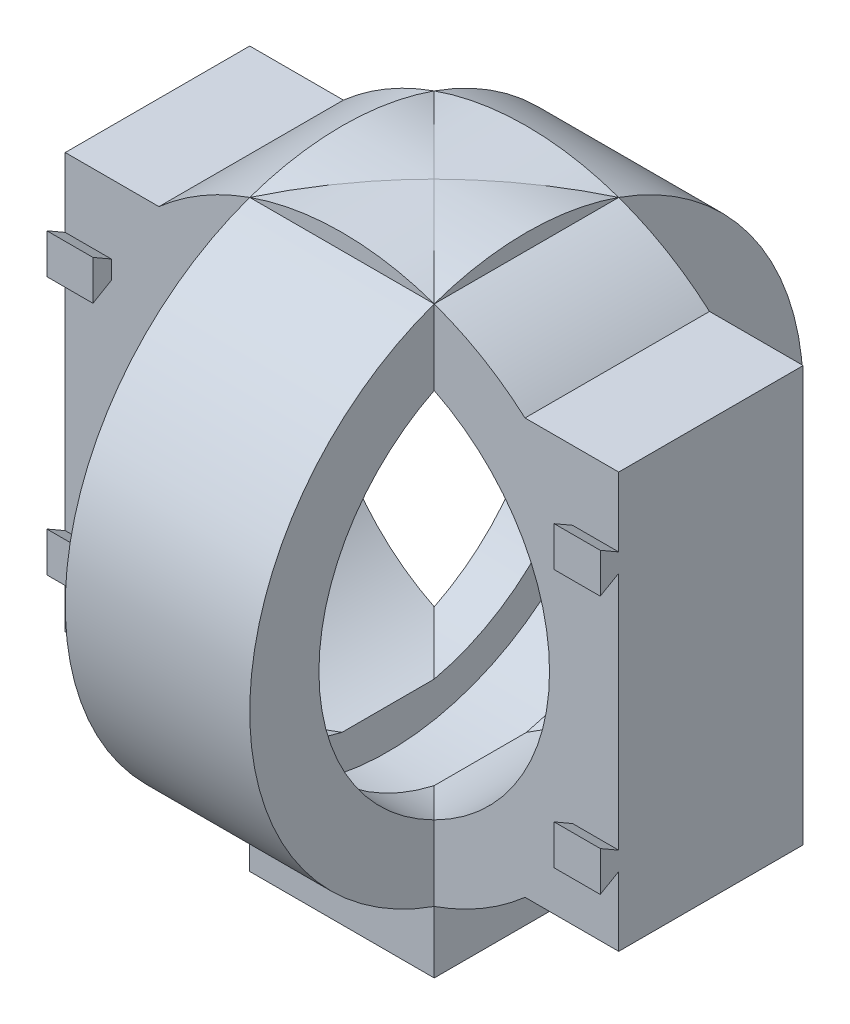
SolidWorks part; units mm, degrees
ref_plane "Plan de face" through (0, 0, 0) normal (0, 0, 1) x (1, 0, 0)
ref_plane "Plan de dessus" through (0, 0, 0) normal (0, 1, 0) x (1, 0, 0)
ref_plane "Plan de droite" through (0, 0, 0) normal (1, 0, 0) x (0, 0, -1)
sketch "Esquisse1" plane through (0, 0, 0) normal (0, 0, 1) x (1, 0, 0)
  circle A0 centre (0, 0) radius 60
  circle A1 centre (0, 0) radius 45
  dimension "D1" = 120
  dimension "D2" = 15
extrude "Boss.-Extru.1" add sketch "Esquisse1" along normal blind 40
ref_plane "Plan1" through (0, -60, 0) normal (0, -1, 0) x (-1, 0, 0)
ref_plane "Plan2" through (60, 0, 0) normal (1, 0, 0) x (0, 0, -1)
sketch "Esquisse5" plane through (60, 0, 0) normal (1, 0, 0) x (0, 0, -1)
  line L0 (-40, 60) -> (-40, -60) construction
  line L1 (-40, 45) -> (0, 45)
  line L2 (-40, 45) -> (-40, -45)
  line L3 (-40, -45) -> (0, -45)
  line L4 (0, 45) -> (0, -45)
  line L5 (0, -60) -> (0, 60) construction
  point P8 (0, 0)
extrude "Boss.-Extru.3" add sketch "Esquisse5" against normal up to surface (20.3137 mm away)
mirror "Symétrie2" about plane through (0, 0, 0) normal (1, 0, 0) of "Boss.-Extru.3"
sketch "Esquisse7" plane through (60, 0, 0) normal (1, 0, 0) x (0, 0, -1)
  line L0 (-40, 30) -> (-40, 26)
  line L1 (-40, 45) -> (-40, -45) construction
  line L2 (-40, 26) -> (-44, 23.6906)
  line L3 (-44, 23.6906) -> (-44, 32.3094)
  line L4 (-44, 32.3094) -> (-40, 30)
  line L5 (0, 0) -> (-40, 0) construction
  line L6 (0, -45) -> (0, 45) construction
  line L7 (-44, -32.3094) -> (-40, -30)
  line L8 (-44, -23.6906) -> (-44, -32.3094)
  line L9 (-40, -26) -> (-44, -23.6906)
  line L10 (-40, -30) -> (-40, -26)
  dimension "D1" = 60
  dimension "D2" = 60
  dimension "D3" = 4
  dimension "D4" = 4
  dimension "D5" = 26
extrude "Boss.-Extru.4" add sketch "Esquisse7" against normal blind 10 contours L4 L0 L2 L3 | L8 L7 L10 L9
mirror "Symétrie3" about plane through (0, 0, 0) normal (1, 0, 0) of "Boss.-Extru.4"
sketch "Esquisse9" plane through (0, 0, 0) normal (1, 0, 0) x (0, 0, -1)
  line L0 (-20, -67.3011) -> (-20, 64.0936) construction
  line L1 (-40, -45) -> (0, -45) construction
  point P4 (-20, -45)
pattern_circular "Répétition circulaire1" count 2 every 90 about axis through (0, -67.3011, 20) along (0, 1, 0) of "Boss.-Extru.1"
ref_plane "Plan3" through (0, 0, 20) normal (0, 0, 1) x (1, 0, 0)
sketch "Esquisse11" plane through (0, 0, 20) normal (0, 0, 1) x (1, 0, 0)
  line L0 (0, -67.3011) -> (0, 64.0936) construction
  line L1 (-10, -37.5) -> (10, -37.5)
  line L2 (-10, -37.5) -> (-10, -52.5)
  line L3 (-10, -52.5) -> (10, -52.5)
  line L4 (10, -37.5) -> (10, -52.5)
  line L5 (-20, 0) -> (20, 0) construction
  line L6 (-20, 56.5685) -> (-20, -56.5685) construction
  line L7 (20, -56.5685) -> (20, 56.5685) construction
  point P7 (0, -37.5)
  dimension "D1" = 15
  dimension "D2" = 52.5
  dimension "D3" = 20
revolve "Enlèvement de matière-Révolution3" cut sketch "Esquisse11" angle 360 about L5
sketch "Esquisse15" plane through (-60, 0, 0) normal (-1, 0, 0) x (0, 0, 1)
  line L0 (20, -72.2671) -> (20, 72.2671) construction
  line L1 (19.75, 66.8805) -> (20.25, 66.8805)
  line L2 (19.75, 66.8805) -> (19.75, -71.0568)
  line L3 (19.75, -71.0568) -> (20.25, -71.0568)
  line L4 (20.25, 66.8805) -> (20.25, -71.0568)
  point P4 (20, 66.8805)
  dimension "D1" = 0.5
ref_plane "Plan5" through (0, -70, 0) normal (0, 1, 0) x (1, 0, 0)
sketch "Esquisse17" plane through (0, -70, 0) normal (0, 1, 0) x (1, 0, 0)
  line L1 (20, 0) -> (-20, 0)
  line L2 (20, 0) -> (20, -40)
  line L3 (20, -40) -> (-20, -40)
  line L4 (-20, 0) -> (-20, -40)
  point P4 (0, 0)
  point P5 (0, 0)
extrude "Boss.-Extru.7" add sketch "Esquisse17" along normal up to surface (13.4315 mm away)
